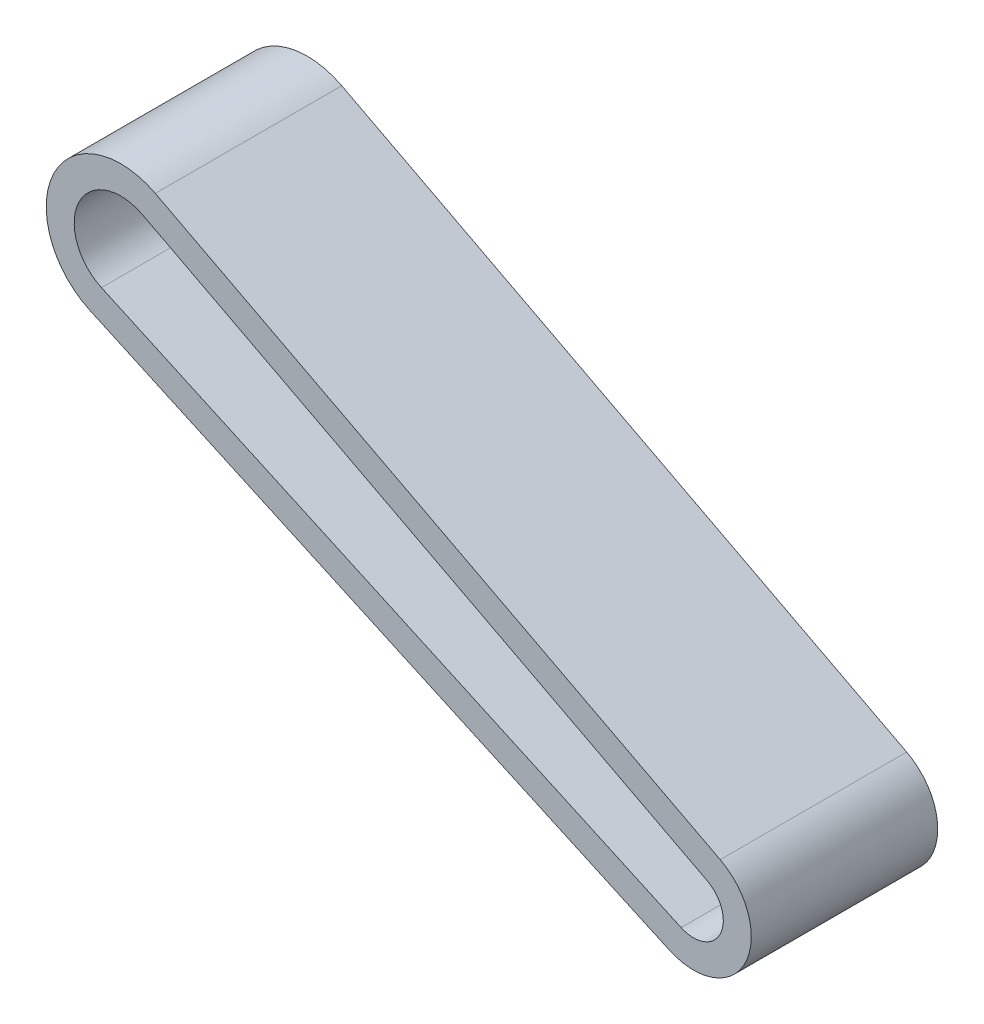
SolidWorks part; units mm, degrees
ref_plane "前视基准面" through (0, 0, 0) normal (0, 0, 1) x (1, 0, 0)
ref_plane "上视基准面" through (0, 0, 0) normal (0, 1, 0) x (1, 0, 0)
ref_plane "右视基准面" through (0, 0, 0) normal (1, 0, 0) x (0, 0, -1)
sketch "Sketch1" plane through (0, 0, 0) normal (0, 0, 1) x (1, 0, 0)
  circle A0 centre (383.6466, 7.5) radius 1.6 construction
  circle A1 centre (352.9296, 22.5) radius 2.5 construction
  circle A2 centre (383.6466, 7.5) radius 1.6
  circle A3 centre (352.9296, 22.5) radius 2.5
sketch "Sketch2" plane through (0, 0, 0) normal (0, 0, 1) x (1, 0, 0)
  line L0 (351.8921, 20.2254) -> (382.9826, 6.0443)
  line L1 (384.3863, 8.9187) -> (354.0854, 24.7168)
  circle A0 centre (383.6466, 7.5) radius 1.6 construction
  circle A1 centre (352.9296, 22.5) radius 2.5 construction
  arc A2 (382.9826, 6.0443) -> (384.3863, 8.9187) centre (383.6466, 7.5) ccw
  arc A3 (354.0854, 24.7168) -> (351.8921, 20.2254) centre (352.9296, 22.5) ccw
  arc A4 (351.8921, 20.2254) -> (354.0854, 24.7168) centre (352.9296, 22.5) ccw construction
  arc A5 (384.3863, 8.9187) -> (382.9826, 6.0443) centre (383.6466, 7.5) ccw construction
  point P4 (0, 0)
  point P10 (351.6569, 20.3482)
extrude "Extrude-Thin1" add sketch "Sketch2" along normal mid plane 10 thin
